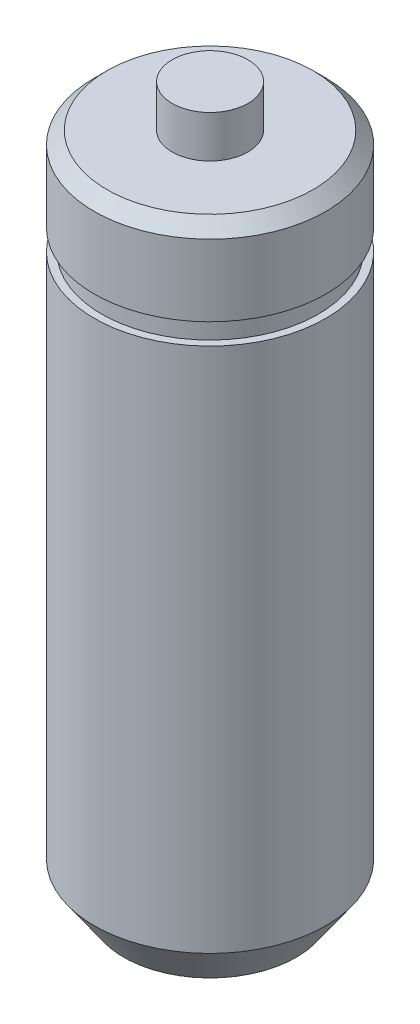
SolidWorks part; units mm, degrees
material "6061 Alloy"
ref_plane "Alzado" through (0, 0, 0) normal (0, 0, 1) x (1, 0, 0)
ref_plane "Planta" through (0, 0, 0) normal (0, 1, 0) x (1, 0, 0)
ref_plane "Vista lateral" through (0, 0, 0) normal (1, 0, 0) x (0, 0, -1)
sketch "Sketch1" plane through (0, 0, 0) normal (0, 0, 1) x (1, 0, 0)
  line L0 (0, 2) -> (1.8, 2)
  line L1 (1.8, 2) -> (1.8, 0)
  line L2 (1.8, 0) -> (4.9, 0)
  line L3 (4.9, 0) -> (5.5, -0.6)
  line L4 (5.5, -0.6) -> (5.5, -4)
  line L5 (5.5, -4) -> (5.15, -4)
  line L6 (5.15, -4) -> (5.15, -5)
  line L7 (5.15, -5) -> (5.5, -5)
  line L8 (5.5, -5) -> (5.5, -30)
  line L9 (5.5, -30) -> (4.1, -32)
  line L10 (4.1, -32) -> (0, -32)
  line L11 (0, -32) -> (0, 2)
  line L12 (0, -36) -> (0, 6) construction
revolve "Carcasa_motor_reductora" add sketch "Sketch1" angle 360 about L12
